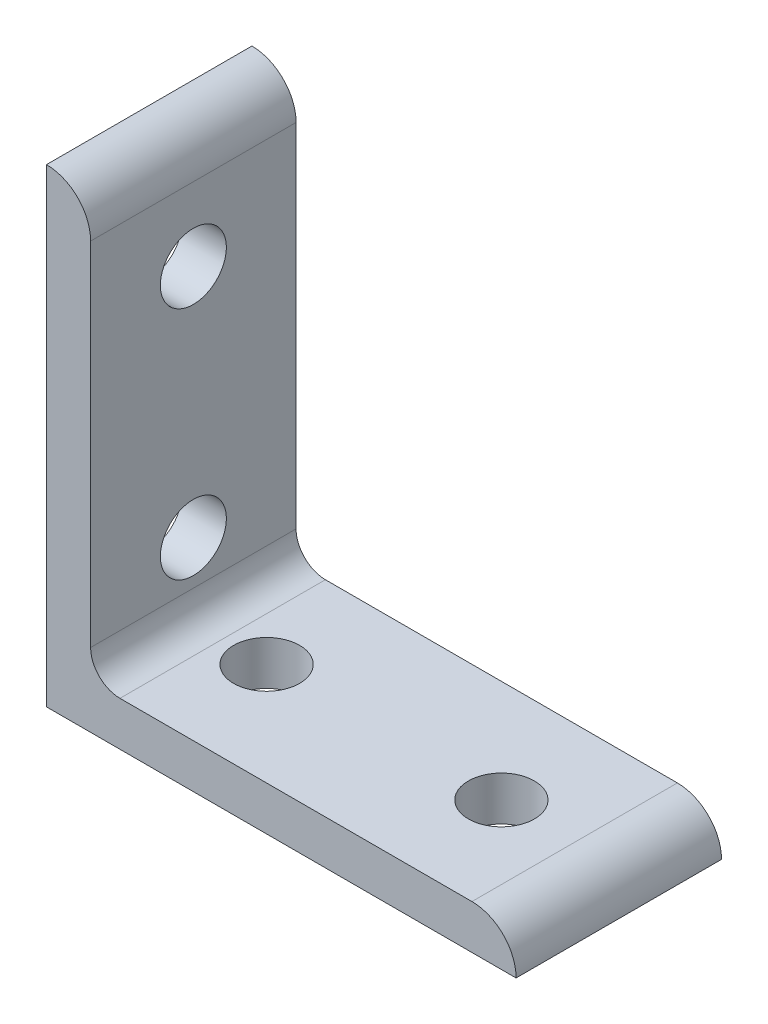
SolidWorks part; units mm, degrees
material "6061-T6 (SS)"
ref_plane "Front Plane" through (0, 0, 0) normal (0, 0, 1) x (1, 0, 0)
ref_plane "Top Plane" through (0, 0, 0) normal (0, 1, 0) x (1, 0, 0)
ref_plane "Right Plane" through (0, 0, 0) normal (1, 0, 0) x (0, 0, -1)
sketch "Sketch1" plane through (0, 0, 0) normal (0, 0, 1) x (1, 0, 0)
  line L0 (0, 0) -> (0, 50.8)
  line L1 (4.7752, 46.0248) -> (4.7752, 50.8) construction
  line L2 (4.7752, 46.0248) -> (4.7752, 7.9502)
  line L3 (7.9502, 4.7752) -> (46.0248, 4.7752)
  line L4 (4.7752, 50.8) -> (0, 50.8) construction
  line L5 (50.8, 0) -> (0, 0)
  line L6 (46.0248, 4.7752) -> (50.8, 4.7752) construction
  line L7 (50.8, 4.7752) -> (50.8, 0) construction
  arc A0 (4.7752, 46.0248) -> (0, 50.8) centre (0, 46.0248) ccw
  arc A1 (50.8, 0) -> (46.0248, 4.7752) centre (46.0248, 0) ccw
  arc A2 (4.7752, 7.9502) -> (7.9502, 4.7752) centre (7.9502, 7.9502) ccw
  point P10 (4.7752, 48.4124)
  dimension "E" = 3.175
  dimension "D" = 4.7752
  dimension "C" = 50.8
  dimension "B" = 50.8
extrude "Boss-Extrude1" add sketch "Sketch1" along normal mid plane 22.225
sketch "Sketch2" plane through (0, 0, 0) normal (0, 1, 0) x (1, 0, 0)
  line L0 (0, 0) -> (12.7, 0) construction
  line L1 (12.7, 0) -> (38.1, 0) construction
  circle A0 centre (12.7, 0) radius 3.5687
  circle A1 centre (38.1, 0) radius 3.5687
extrude "Cut-Extrude1" cut sketch "Sketch2" along normal through all
sketch "Sketch3" plane through (0, 0, 0) normal (1, 0, 0) x (0, 0, -1)
  line L0 (0, 0) -> (0, 12.7) construction
  line L1 (0, 12.7) -> (0, 38.1) construction
  circle A0 centre (0, 12.7) radius 3.5687
  circle A1 centre (0, 38.1) radius 3.5687
  dimension "D1" = 12.7
  dimension "D2" = 25.4
extrude "Cut-Extrude2" cut sketch "Sketch3" along normal through all
equation "\"E@Sketch3\" = \"E@Sketch2\""
equation "\"D1@Sketch3\" = \"D1@Sketch2\""
equation "\"D2@Sketch3\" = \"D2@Sketch2\""
